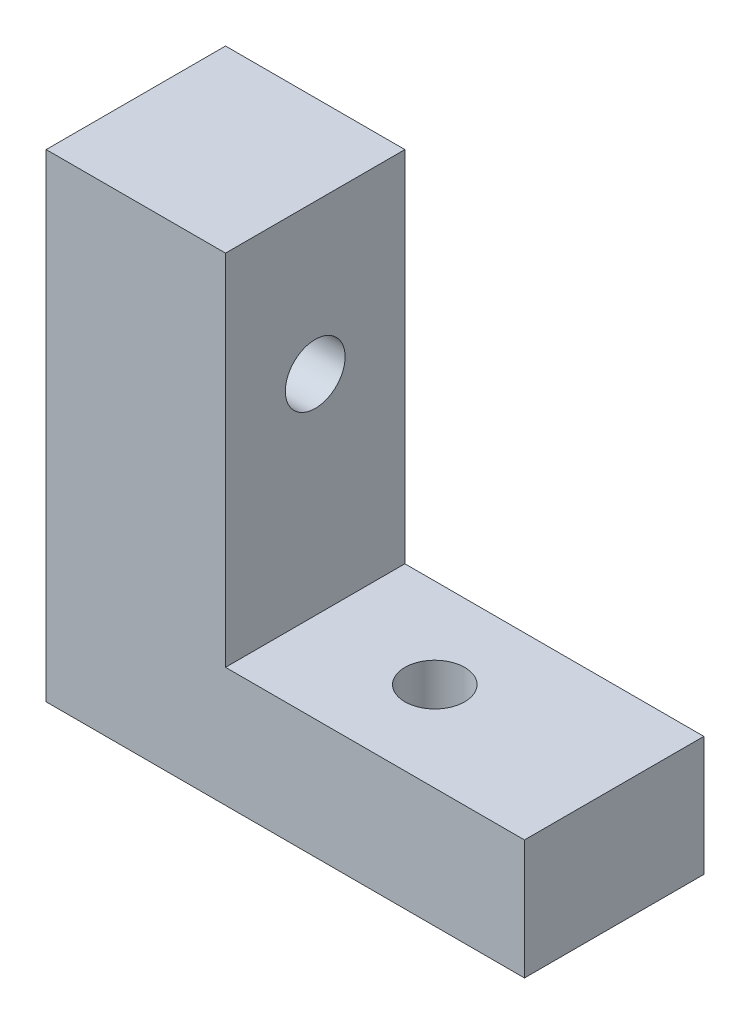
SolidWorks part; units mm, degrees
ref_plane "Front Plane" through (0, 0, 0) normal (0, 0, 1) x (1, 0, 0)
ref_plane "Top Plane" through (0, 0, 0) normal (0, 1, 0) x (1, 0, 0)
ref_plane "Right Plane" through (0, 0, 0) normal (1, 0, 0) x (0, 0, -1)
sketch "Sketch1" plane through (0, 0, 0) normal (0, 0, 1) x (1, 0, 0)
  line L1 (0, 0) -> (30, 0)
  line L2 (0, 0) -> (0, -80)
  line L3 (0, -80) -> (30, -80)
  line L4 (30, 0) -> (30, -60)
  line L5 (30, -80) -> (80, -80)
  line L7 (30, -60) -> (80, -60)
  line L8 (80, -80) -> (80, -60)
extrude "Boss-Extrude1" add sketch "Sketch1" along normal blind 30
sketch "Sketch2" plane through (30, 0, 0) normal (1, 0, 0) x (0, 0, -1)
  line L0 (-15, 0) -> (-15, -25) construction
  line L1 (-30, 0) -> (0, 0) construction
  circle A0 centre (-15, -25) radius 5
extrude "Cut-Extrude2" cut sketch "Sketch2" against normal blind 40
sketch "Sketch4" plane through (0, -60, 0) normal (0, 1, 0) x (1, 0, 0)
  line L0 (30, -15) -> (50, -15)
  line L1 (30, -30) -> (30, 0) construction
  circle A0 centre (50, -15) radius 5
extrude "Cut-Extrude3" cut sketch "Sketch4" against normal blind 40
